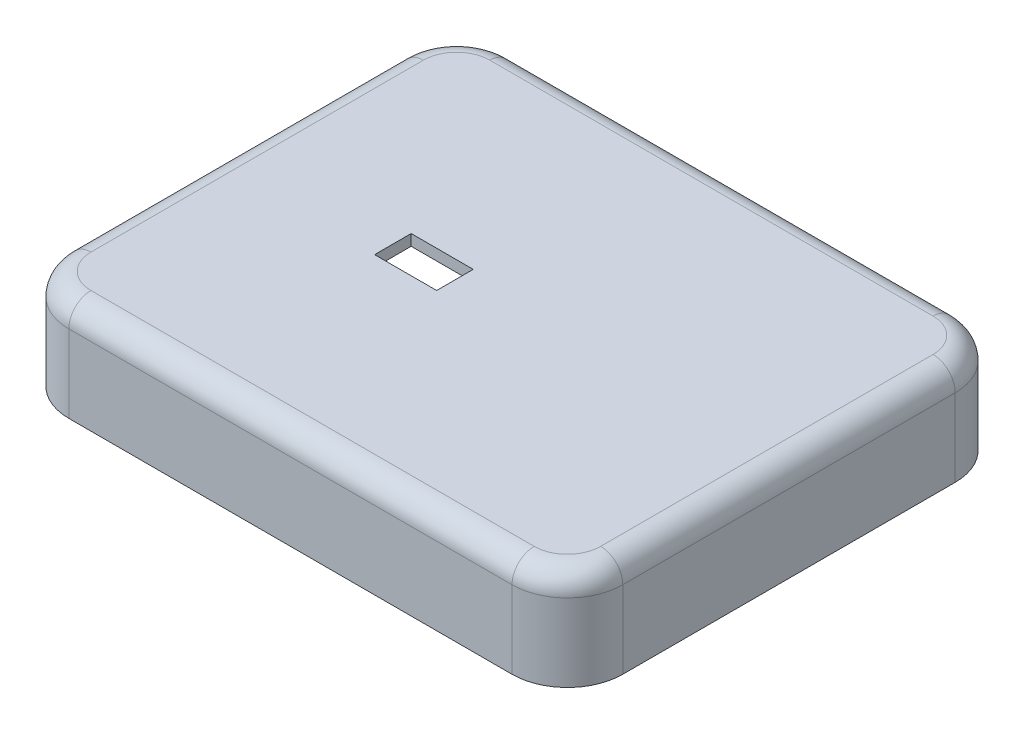
SolidWorks part; units mm, degrees
ref_plane "Front Plane" through (0, 0, 0) normal (0, 0, 1) x (1, 0, 0)
ref_plane "Top Plane" through (0, 0, 0) normal (0, 1, 0) x (1, 0, 0)
ref_plane "Right Plane" through (0, 0, 0) normal (1, 0, 0) x (0, 0, -1)
sketch "Sketch1" plane through (0, 0, 0) normal (0, 1, 0) x (1, 0, 0)
  line L1 (-34.5408, 21.1097) -> (5.4592, 21.1097)
  line L2 (-39.5408, 16.1097) -> (-39.5408, -13.8903)
  line L3 (-34.5408, -18.8903) -> (5.4592, -18.8903)
  line L4 (10.4592, 16.1097) -> (10.4592, -13.8903)
  arc A0 (5.4592, -18.8903) -> (10.4592, -13.8903) centre (5.4592, -13.8903) ccw
  arc A1 (-39.5408, -13.8903) -> (-34.5408, -18.8903) centre (-34.5408, -13.8903) ccw
  arc A2 (-34.5408, 21.1097) -> (-39.5408, 16.1097) centre (-34.5408, 16.1097) ccw
  arc A3 (5.4592, 21.1097) -> (10.4592, 16.1097) centre (5.4592, 16.1097) cw
  point P6 (10.4592, -18.8903)
  point P11 (-39.5408, 21.1097)
  point P14 (10.4592, 21.1097)
  dimension "D3" = 5
  dimension "D1" = 50
  dimension "D2" = 40
extrude "Boss-Extrude1" add sketch "Sketch1" along normal blind 9
fillet "Fillet1" radius 2 8 edges at (-38.0764, 9, -19.6452) (-39.5408, 9, -1.1097) (-38.0764, 9, 17.4258) (-14.5408, 9, 18.8903) (8.9947, 9, 17.4258) (10.4592, 9, -1.1097) (8.9947, 9, -19.6452) (-14.5408, 9, -21.1097)
sketch "Sketch2" plane through (0, 0, 0) normal (0, -1, 0) x (1, 0, 0)
  line L0 (10.4592, 13.8903) -> (10.4592, -16.1097) construction
  line L1 (-32.1408, 16.4903) -> (3.0592, 16.4903)
  line L2 (-37.1408, 11.4903) -> (-37.1408, -13.7097)
  line L3 (-32.1408, -18.7097) -> (3.0592, -18.7097)
  line L4 (8.0592, 11.4903) -> (8.0592, -13.7097)
  line L5 (-39.5408, -16.1097) -> (-39.5408, 13.8903) construction
  line L6 (5.4592, -21.1097) -> (-34.5408, -21.1097) construction
  line L7 (-34.5408, 18.8903) -> (5.4592, 18.8903) construction
  arc A0 (3.0592, -18.7097) -> (8.0592, -13.7097) centre (3.0592, -13.7097) ccw
  arc A1 (-37.1408, -13.7097) -> (-32.1408, -18.7097) centre (-32.1408, -13.7097) ccw
  arc A2 (-32.1408, 16.4903) -> (-37.1408, 11.4903) centre (-32.1408, 11.4903) ccw
  arc A3 (3.0592, 16.4903) -> (8.0592, 11.4903) centre (3.0592, 11.4903) cw
  dimension "D5" = 5
  dimension "D1" = 2.4
  dimension "D2" = 2.4
  dimension "D3" = 2.4
  dimension "D4" = 2.4
extrude "Cut-Extrude1" cut sketch "Sketch2" against normal blind 7
sketch "Sketch3" plane through (0, 0, 0) normal (0, -1, 0) x (1, 0, 0)
  line L0 (10.4592, 13.8903) -> (10.4592, -16.1097) construction
  line L1 (-34.5408, 18.8903) -> (5.4592, 18.8903) construction
  circle A0 centre (7.6592, 16.0903) radius 1.1
  circle A1 centre (-36.7408, 16.0903) radius 1.1
  circle A2 centre (-36.7408, -18.3097) radius 1.1
  circle A3 centre (7.6592, -18.3097) radius 1.1
  dimension "D1" = 2.2
  dimension "D2" = 2.8
  dimension "D3" = 2.8
  dimension "D4" = 2
  dimension "D5" = 2
extrude "Cut-Extrude2" cut sketch "Sketch3" against normal blind 6
sketch "Sketch4" plane through (0, 7, 0) normal (0, -1, 0) x (1, 0, 0)
  line L0 (-34.5408, 18.8903) -> (5.4592, 18.8903) construction
  line L1 (-24.5408, 1.2903) -> (-18.9408, 1.2903)
  line L2 (-24.5408, 1.2903) -> (-24.5408, -2.0097)
  line L3 (-24.5408, -2.0097) -> (-18.9408, -2.0097)
  line L4 (-18.9408, 1.2903) -> (-18.9408, -2.0097)
  line L5 (-39.5408, -16.1097) -> (-39.5408, 13.8903) construction
  dimension "D1" = 5.6
  dimension "D2" = 3.3
  dimension "D3" = 17.6
  dimension "D4" = 15
extrude "Cut-Extrude3" cut sketch "Sketch4" against normal through all
sketch "Sketch5" plane through (0, 7, 0) normal (0, -1, 0) x (1, 0, 0)
  line L0 (-18.9408, -2.0097) -> (-18.9408, 1.2903) construction
  line L1 (-25.5408, 2.2903) -> (-17.9408, 2.2903)
  line L2 (-25.5408, 2.2903) -> (-25.5408, -3.0097)
  line L3 (-25.5408, -3.0097) -> (-17.9408, -3.0097)
  line L4 (-17.9408, 2.2903) -> (-17.9408, -3.0097)
  line L5 (-24.5408, 1.2903) -> (-24.5408, -2.0097) construction
  line L6 (-18.9408, 1.2903) -> (-24.5408, 1.2903) construction
  line L7 (-24.5408, -2.0097) -> (-18.9408, -2.0097) construction
  dimension "D1" = 1
  dimension "D2" = 1
  dimension "D3" = 1
  dimension "D4" = 1
extrude "Cut-Extrude4" cut sketch "Sketch5" against normal blind 1
sketch "Sketch6" plane through (0, 7, 0) normal (0, -1, 0) x (1, 0, 0)
  line L0 (-17.9408, -3.0097) -> (-17.9408, 2.2903) construction
  line L1 (-17.9408, 2.2903) -> (-25.5408, 2.2903) construction
  circle A0 centre (-17.4408, 6.6403) radius 1.2
  circle A1 centre (-31.4408, 6.6403) radius 1.2
  circle A2 centre (-31.4408, -7.3597) radius 1.2
  circle A3 centre (-17.4408, -7.3597) radius 1.2
  dimension "D2" = 2.4
  dimension "D5" = 4.35
  dimension "D1" = 0.5
  dimension "D3" = 2
  dimension "D4" = 2
extrude "Boss-Extrude2" add sketch "Sketch6" along normal blind 3.5
sketch "Sketch7" plane through (0, 3.5, 0) normal (0, -1, 0) x (1, 0, 0)
  line L1 (-30.4408, 6.6403) -> (-18.4408, 6.6403)
  line L2 (-31.4408, 5.6403) -> (-31.4408, -6.2064)
  line L3 (-30.4408, -7.2064) -> (-18.4408, -7.2064)
  line L4 (-17.4408, 5.6403) -> (-17.4408, -6.2064)
  circle A0 centre (-17.4408, -7.3597) radius 1.2 construction
  arc A1 (-18.4408, -7.2064) -> (-17.4408, -6.2064) centre (-18.4408, -6.2064) ccw
  arc A2 (-31.4408, -6.2064) -> (-30.4408, -7.2064) centre (-30.4408, -6.2064) ccw
  arc A3 (-30.4408, 6.6403) -> (-31.4408, 5.6403) centre (-30.4408, 5.6403) ccw
  arc A4 (-18.4408, 6.6403) -> (-17.4408, 5.6403) centre (-18.4408, 5.6403) cw
  point P13 (-31.4408, 6.6403)
  dimension "D1" = 0
  dimension "D2" = 1
extrude "Cut-Extrude5" cut sketch "Sketch7" against normal blind 3.5
sketch "Sketch9" plane through (0, 7, 0) normal (0, -1, 0) x (1, 0, 0)
  line L0 (8.0592, -13.7097) -> (8.0592, 11.4903) construction
  line L1 (-32.1408, -18.7097) -> (3.0592, -18.7097) construction
  line L2 (-15.2599, -8.6193) -> (-15.2599, -11.8116)
  line L3 (2.5717, -8.6193) -> (4.4033, -8.6193)
  line L4 (2.5717, -8.6193) -> (2.5717, -11.8116)
  line L5 (2.5717, -11.8116) -> (4.4033, -11.8116)
  line L6 (4.4033, -8.6193) -> (4.4033, -11.8116)
  line L7 (-15.2599, -8.6193) -> (-13.4283, -8.6193)
  line L8 (-13.4283, -8.6193) -> (-13.4283, -11.8116)
  line L9 (-15.2599, -11.8116) -> (-13.4283, -11.8116)
  circle A0 centre (3.0592, 9.2903) radius 1.2
  circle A1 centre (-14.1408, 9.2903) radius 1.2
  dimension "D1" = 2.4
  dimension "D2" = 5
  dimension "D3" = 28
  dimension "D6" = 16
  dimension "D4" = 2
  dimension "D5" = 2
extrude "Boss-Extrude3" add sketch "Sketch9" along normal blind 3.5
sketch "Sketch10" plane through (0, 3.5, 0) normal (0, -1, 0) x (1, 0, 0)
  line L0 (2.5717, -11.8116) -> (4.4033, -11.8116) construction
  line L1 (-14.1408, 9.2903) -> (3.0592, 9.2903)
  line L2 (-14.1408, 9.2903) -> (-14.1408, -11.8116)
  line L3 (-14.1408, -11.8116) -> (3.0592, -11.8116)
  line L4 (3.0592, 9.2903) -> (3.0592, -11.8116)
  circle A0 centre (3.0592, 9.2903) radius 1.2 construction
  dimension "D1" = 0
extrude "Cut-Extrude7" cut sketch "Sketch10" against normal blind 3.5 contours L2 L3 L4 L1
sketch "Sketch11" plane through (0, 0, -18.7097) normal (0, 0, 1) x (1, 0, 0)
  line L1 (-9.5408, 7.15) -> (-1.5408, 7.15)
  line L2 (-10.0408, 6.65) -> (-10.0408, 4.25)
  line L3 (-9.5408, 3.75) -> (-1.5408, 3.75)
  line L4 (-1.0408, 6.65) -> (-1.0408, 4.25)
  line L7 (-32.1408, 7) -> (3.0592, 7) construction
  arc A0 (-10.0408, 4.25) -> (-9.5408, 3.75) centre (-9.5408, 4.25) ccw
  arc A1 (-9.5408, 7.15) -> (-10.0408, 6.65) centre (-9.5408, 6.65) ccw
  arc A2 (-1.5408, 3.75) -> (-1.0408, 4.25) centre (-1.5408, 4.25) ccw
  arc A3 (-1.5408, 7.15) -> (-1.0408, 6.65) centre (-1.5408, 6.65) cw
  point P8 (-10.0408, 7.15)
  point P11 (-1.0408, 3.75)
  point P14 (-1.0408, 7.15)
  dimension "D3" = 0.5
  dimension "D1" = 9
  dimension "D2" = 3.4
  dimension "D4" = 0.15
extrude "Cut-Extrude8" cut sketch "Sketch11" against normal blind 3.5 contours L4 A2 L3 A0 L2 A1 L1 A3
